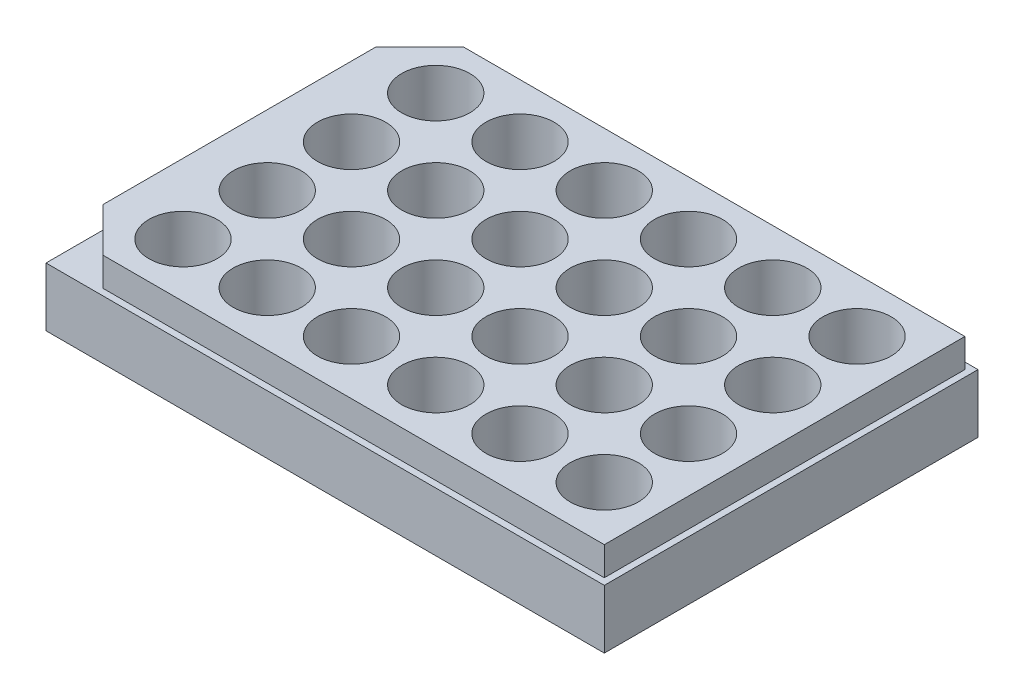
SolidWorks part; units mm, degrees
material "PVC Rigid"
ref_plane "Front Plane" through (0, 0, 0) normal (0, 0, 1) x (1, 0, 0)
ref_plane "Top Plane" through (0, 0, 0) normal (0, 1, 0) x (1, 0, 0)
ref_plane "Right Plane" through (0, 0, 0) normal (1, 0, 0) x (0, 0, -1)
sketch "Sketch1" plane through (0, 0, 0) normal (0, 1, 0) x (1, 0, 0)
  line L1 (-63.945, 42.8) -> (63.945, 42.8)
  line L2 (-63.945, 42.8) -> (-63.945, -42.8)
  line L3 (-63.945, -42.8) -> (63.945, -42.8)
  line L4 (63.945, 42.8) -> (63.945, -42.8)
  line L5 (-63.945, 42.8) -> (63.945, -42.8) construction
  line L6 (-63.945, -42.8) -> (63.945, 42.8) construction
  point P0 (0, 0)
  dimension "D1" = 127.89
  dimension "D2" = 85.6
extrude "Main Plate" add sketch "Sketch1" along normal blind 20.02
sketch "Wells_LSP" plane through (0, 20.02, 0) normal (0, 1, 0) x (1, 0, 0)
  line L0 (-46.425, 28.96) -> (-27.125, 28.96) construction
  line L4 (63.945, 42.8) -> (-63.945, 42.8) construction
  line L5 (-63.945, 42.8) -> (-63.945, -42.8) construction
  circle A0 centre (-46.425, 28.96) radius 7.81
  circle A1 centre (-27.125, 28.96) radius 7.81
  circle A2 centre (-7.825, 28.96) radius 7.81
  circle A3 centre (11.475, 28.96) radius 7.81
  circle A4 centre (30.775, 28.96) radius 7.81
  circle A5 centre (50.075, 28.96) radius 7.81
  circle A6 centre (-27.125, 9.66) radius 7.81
  circle A7 centre (-7.825, 9.66) radius 7.81
  circle A8 centre (11.475, 9.66) radius 7.81
  circle A9 centre (30.775, 9.66) radius 7.81
  circle A10 centre (50.075, 9.66) radius 7.81
  circle A11 centre (-27.125, -9.64) radius 7.81
  circle A12 centre (-7.825, -9.64) radius 7.81
  circle A13 centre (11.475, -9.64) radius 7.81
  circle A14 centre (30.775, -9.64) radius 7.81
  circle A15 centre (50.075, -9.64) radius 7.81
  circle A16 centre (-27.125, -28.94) radius 7.81
  circle A17 centre (-7.825, -28.94) radius 7.81
  circle A18 centre (11.475, -28.94) radius 7.81
  circle A19 centre (30.775, -28.94) radius 7.81
  circle A20 centre (50.075, -28.94) radius 7.81
  circle A21 centre (-46.425, 9.66) radius 7.81
  circle A22 centre (-46.425, -9.64) radius 7.81
  circle A23 centre (-46.425, -28.94) radius 7.81
  dimension "D2" = 6
  dimension "D4" = 4
  dimension "D7" = 15.62
  dimension "D16" = 17.52
  dimension "D3" = 19.3
  dimension "D15" = 13.84
extrude "Wells Depth" cut sketch "Wells_LSP" against normal through all
sketch "Sketch7" plane through (0, 20.02, 0) normal (0, 1, 0) x (1, 0, 0)
  line L0 (62.445, 41.3) -> (-62.445, 41.3)
  line L1 (63.945, 42.8) -> (-63.945, 42.8)
  line L2 (63.945, 42.8) -> (63.945, -42.8)
  line L3 (63.945, -42.8) -> (-63.945, -42.8)
  line L4 (-63.945, 42.8) -> (-63.945, -42.8)
  line L5 (-62.445, 41.3) -> (-62.445, -41.3)
  line L6 (62.445, -41.3) -> (-62.445, -41.3)
  line L7 (62.445, 41.3) -> (62.445, -41.3)
  point P0 (0, 0)
  dimension "D1" = 1.5
extrude "Flange" cut sketch "Sketch7" against normal blind 6.57
sketch "Style Sketch" plane through (0, 20.02, 0) normal (0, 1, 0) x (1, 0, 0)
  line L0 (-62.445, 41.3) -> (-52.445, 41.3)
  line L1 (62.445, 41.3) -> (-62.445, 41.3) construction
  line L2 (-52.445, 41.3) -> (-62.445, 31.3)
  line L3 (-62.445, 41.3) -> (-62.445, -41.3) construction
  line L4 (-62.445, 31.3) -> (-62.445, 41.3)
  line L5 (-62.445, -41.3) -> (-52.445, -41.3)
  line L6 (-62.445, -41.3) -> (62.445, -41.3) construction
  line L7 (-62.445, -41.3) -> (-62.445, -31.3)
  line L8 (-62.445, -31.3) -> (-52.445, -41.3)
  dimension "D1" = 10
  dimension "D2" = 10
  dimension "D3" = 10
  dimension "D4" = 10
extrude "Style <3" cut sketch "Style Sketch" against normal blind 6.57
equation "\"D1\"= 0.32"
equation "\"D1\"= 1.27 - 0.32"
